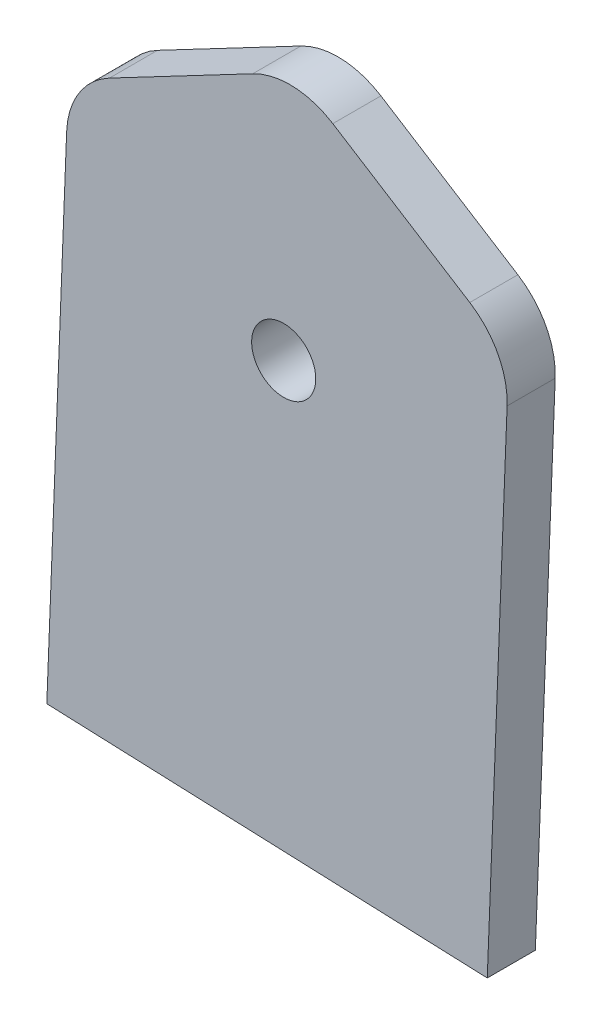
SolidWorks part; units mm, degrees
ref_plane "Front Plane" through (0, 0, 0) normal (0, 0, 1) x (1, 0, 0)
ref_plane "Top Plane" through (0, 0, 0) normal (0, 1, 0) x (1, 0, 0)
ref_plane "Right Plane" through (0, 0, 0) normal (1, 0, 0) x (0, 0, -1)
sketch "Sketch1" plane through (0, 0, 0) normal (0, 0, 1) x (1, 0, 0)
  line L0 (-200.2134, 335.2788) -> (-182.3304, 344.6881)
  line L1 (-172.3381, 344.2957) -> (-155.248, 333.5132)
  line L5 (-208.0251, 263.77) -> (-153.0675, 261.612)
  line L6 (-153.0675, 261.612) -> (-150.5917, 324.6635)
  line L9 (-205.5493, 326.8214) -> (-208.0251, 263.77)
  circle A0 centre (-178.467, 315.6439) radius 4
  arc A1 (-205.5493, 326.8214) -> (-200.2134, 335.2788) centre (-195.557, 326.4291) cw
  arc A2 (-182.3304, 344.6881) -> (-172.3381, 344.2957) centre (-177.6741, 335.8383) cw
  arc A3 (-155.248, 333.5132) -> (-150.5917, 324.6635) centre (-160.584, 325.0558) cw
  point P11 (-177.2817, 345.8306)
  point P14 (0, 0)
  dimension "D1" = 10
  dimension "D2" = 60
  dimension "D8" = 261.612
  dimension "D11" = 8
  dimension "D3" = 60
  dimension "D4" = 60
  dimension "D5" = 90
  dimension "D6" = 55
  dimension "D7" = 63.1
  dimension "D9" = 153.0675
  dimension "D10" = 255.4048
  dimension "D12" = 30.21
  dimension "D13" = 27.5
extrude "Boss-Extrude1" add sketch "Sketch1" along normal blind 6 separate body
